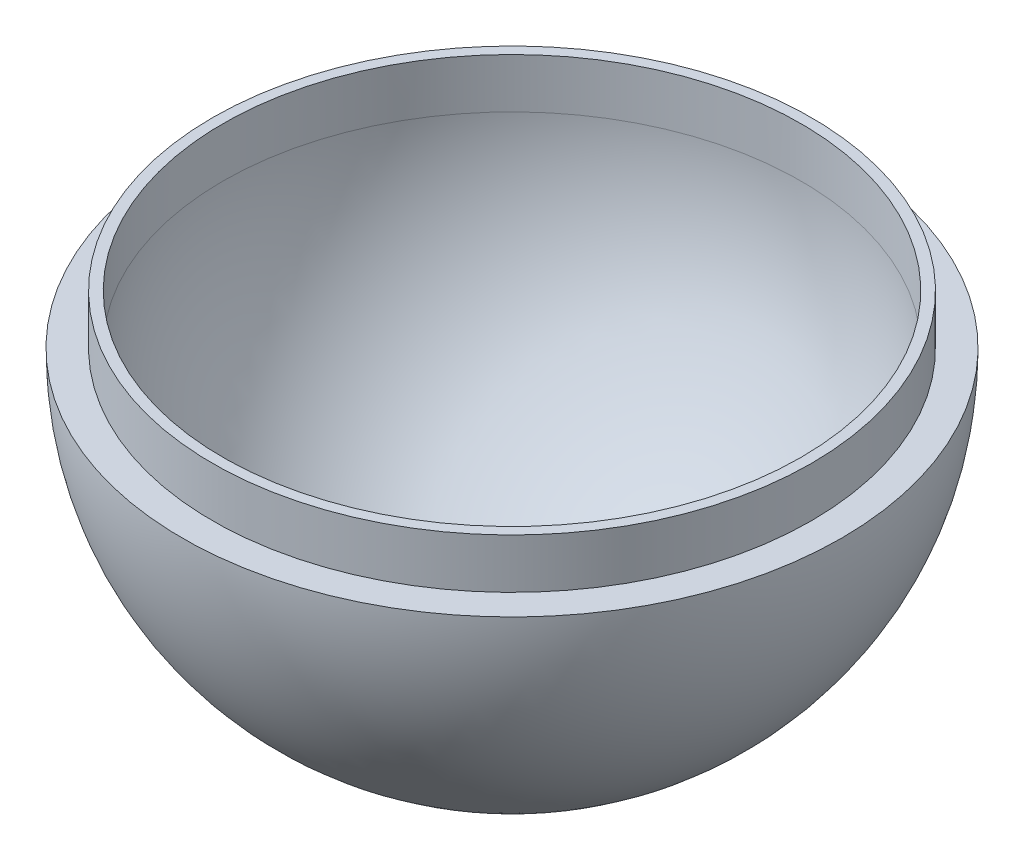
SolidWorks part; units mm, degrees
ref_plane "Front Plane" through (0, 0, 0) normal (0, 0, 1) x (1, 0, 0)
ref_plane "Top Plane" through (0, 0, 0) normal (0, 1, 0) x (1, 0, 0)
ref_plane "Right Plane" through (0, 0, 0) normal (1, 0, 0) x (0, 0, -1)
sketch "Sketch1" plane through (0, 0, 0) normal (0, 0, 1) x (1, 0, 0)
  line L0 (0, -25) -> (0, -28.5034)
  line L1 (0, -29.2468) -> (0, 5.9032) construction
  line L2 (-25.9, 4.3) -> (-25.9, 2.5)
  line L3 (-30.1252, 0) -> (2.196, 0) construction
  line L4 (-25.9, 2) -> (-25.9, 2.5)
  line L9 (-25.9, 4.3) -> (-25, 4.3)
  line L10 (-25, 4.3) -> (-25, 0)
  line L11 (-28.5034, 0) -> (-25.9, 0)
  line L17 (-25.9, 2) -> (-25.9, 0)
  arc A0 (-25, 0) -> (-22.9825, -9.8389) centre (0, 0) ccw
  arc A1 (-28.5034, 0) -> (0, -28.5034) centre (0, 0) ccw
  arc A2 (-22.9825, -9.8389) -> (-22.5, -10.8972) centre (0, 0) ccw
  arc A3 (-11.2905, -22.3053) -> (0, -25) centre (0, 0) ccw
  arc A4 (-21.2448, -13.178) -> (-13.2101, -21.2249) centre (0, 0) ccw
  arc A5 (-11.2905, -22.3053) -> (-13.2101, -21.2249) centre (0, 0) cw
  arc A6 (-21.2448, -13.178) -> (-22.5, -10.8972) centre (0, 0) cw
  dimension "D1" = 3.5034
  dimension "D2" = 4.3
  dimension "D3" = 25
  dimension "D4" = 25
  dimension "D5" = 28.5034
  dimension "D9" = 0.9
  dimension "D10" = 2.6034
revolve "Revolve2" add sketch "Sketch1" angle 360 about L1
